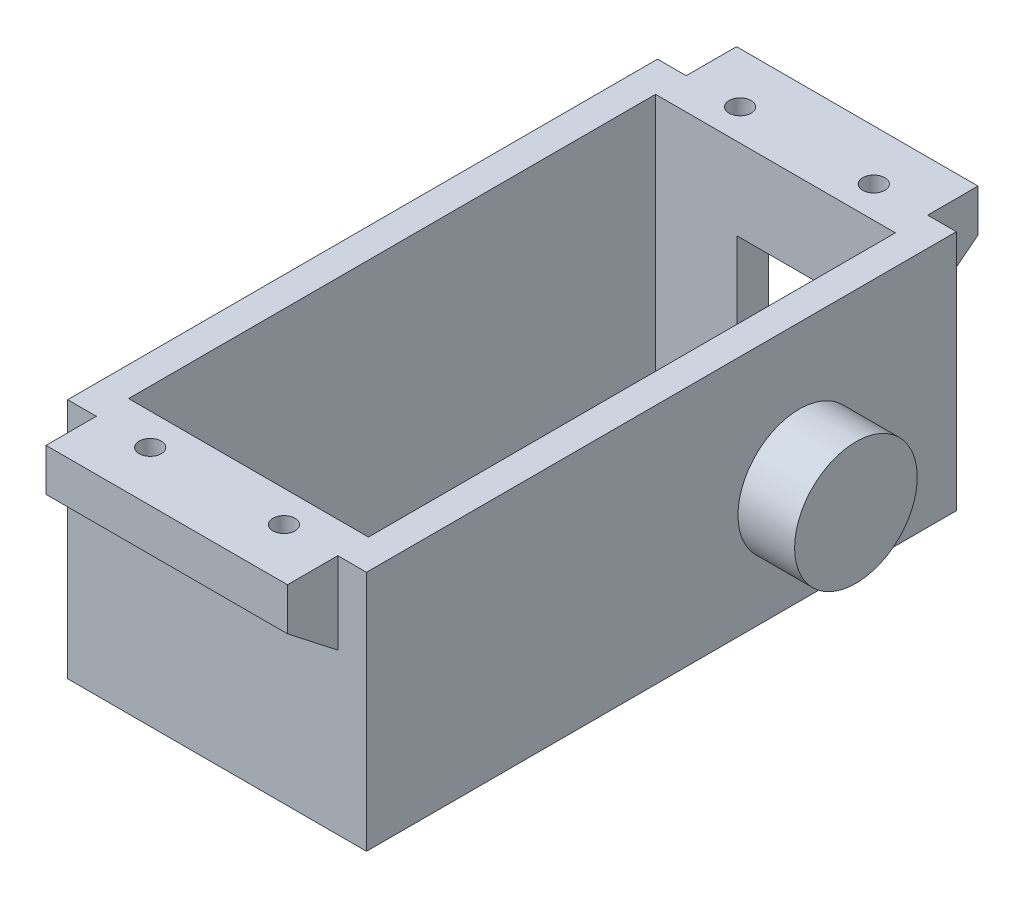
SolidWorks part; units mm, degrees
ref_plane "前视基准面" through (0, 0, 0) normal (0, 0, 1) x (1, 0, 0)
ref_plane "上视基准面" through (0, 0, 0) normal (0, 1, 0) x (1, 0, 0)
ref_plane "右视基准面" through (0, 0, 0) normal (1, 0, 0) x (0, 0, -1)
other "Configuration Table"
sketch "草图1" plane through (0, 0, 0) normal (0, 1, 0) x (1, 0, 0)
  line L1 (19, -37.5) -> (-19, -37.5)
  line L2 (19, -37.5) -> (19, 37.5)
  line L3 (19, 37.5) -> (-19, 37.5)
  line L4 (-19, -37.5) -> (-19, 37.5)
  line L5 (19, -37.5) -> (-19, 37.5) construction
  line L6 (19, 37.5) -> (-19, -37.5) construction
  point P0 (0, 0)
  dimension "D1" = 75
  dimension "D2" = 38
extrude "凸台-拉伸1" add sketch "草图1" along normal blind 30.73
sketch "草图2" plane through (-19, 0, 0) normal (-1, 0, 0) x (0, 0, 1)
  line L1 (-37.5, 30.73) -> (-37.5, 0) construction
  line L3 (-37.5, 0) -> (37.5, 0) construction
  circle A0 centre (-17.53, 13.39) radius 7.8
  point P2 (-17.53, 21.19)
  point P3 (-17.53, 5.59)
  point P4 (-25.33, 13.39)
  point P5 (-9.73, 13.39)
  point P10 (0, 0)
  dimension "D2" = 15.6
  dimension "D1" = 12.17
  dimension "D3" = 5.59
extrude "凸台-拉伸2" add sketch "草图2" along normal blind 7.2
sketch "草图3" plane through (0, 0, -37.5) normal (0, 0, -1) x (-1, 0, 0)
  line L0 (-19, 30.73) -> (19, 30.73) construction
  line L1 (15.35, 20.33) -> (-15.35, 20.33)
  line L2 (15.35, 20.33) -> (15.35, 30.73)
  line L3 (15.35, 30.73) -> (-15.35, 30.73)
  line L4 (-15.35, 20.33) -> (-15.35, 30.73)
  line L5 (15.35, 20.33) -> (-15.35, 30.73) construction
  line L6 (15.35, 30.73) -> (-15.35, 20.33) construction
  point P0 (0, 25.53)
  point P7 (0, 0)
  dimension "D1" = 30.7
  dimension "D2" = 10.4
extrude "凸台-拉伸3" add sketch "草图3" along normal blind 6.4
sketch "草图5" plane through (0, 30.73, 0) normal (0, 1, 0) x (1, 0, 0)
  line L1 (15.25, -33.5) -> (-15.25, -33.5)
  line L2 (15.25, -33.5) -> (15.25, 33.5)
  line L3 (15.25, 33.5) -> (-15.25, 33.5)
  line L4 (-15.25, -33.5) -> (-15.25, 33.5)
  line L5 (15.25, -33.5) -> (-15.25, 33.5) construction
  line L6 (15.25, 33.5) -> (-15.25, -33.5) construction
  point P0 (0, 0)
  dimension "D1" = 67
  dimension "D2" = 30.5
extrude "切除-拉伸1" cut sketch "草图5" against normal through all
mirror "镜向2" about plane through (0, 0, 0) normal (1, 0, 0) of "凸台-拉伸2"
sketch "草图6" plane through (0, 0, -37.5) normal (0, 0, -1) x (-1, 0, 0)
  line L0 (-19, 0) -> (19, 0) construction
  line L1 (4.9, 0) -> (-4.9, 0)
  line L2 (4.9, 0) -> (4.9, 20.33)
  line L3 (4.9, 20.33) -> (-4.9, 20.33)
  line L4 (-4.9, 0) -> (-4.9, 20.33)
  line L5 (4.9, 0) -> (-4.9, 20.33) construction
  line L6 (4.9, 20.33) -> (-4.9, 0) construction
  line L7 (-15.35, 20.33) -> (15.35, 20.33) construction
  point P0 (0, 10.165)
  point P7 (0, 0)
  dimension "D1" = 9.8
extrude "切除-拉伸2" cut sketch "草图6" against normal up to next
sketch "草图7" plane through (15.35, 0, 0) normal (1, 0, 0) x (0, 0, -1)
  line L0 (37.5, 20.33) -> (43.9, 25.3302)
  line L1 (43.9, 30.73) -> (43.9, 20.33) construction
  line L2 (43.9, 25.3302) -> (43.9, 20.33)
  line L3 (43.9, 20.33) -> (37.5, 20.33) construction
  line L4 (43.9, 20.33) -> (37.5, 20.33)
  line L5 (37.5, 30.73) -> (37.5, 0) construction
  dimension "D1" = 128
extrude "切除-拉伸3" cut sketch "草图7" against normal up to next
mirror "镜向4" about plane through (0, 0, 0) normal (0, 0, 1) of "切除-拉伸3", "凸台-拉伸3"
sketch "草图8" plane through (0, 30.73, 0) normal (0, 1, 0) x (1, 0, 0)
  line L0 (-15.35, 37.5) -> (15.35, 37.5) construction
  line L1 (19, 37.5) -> (15.35, 37.5) construction
  line L2 (0, 37.5) -> (0, 43.9) construction
  line L3 (-15.35, 43.9) -> (15.35, 43.9) construction
  line L4 (-19, 0) -> (19, 0) construction
  line L5 (-19, 37.5) -> (-19, -37.5) construction
  line L6 (19, -37.5) -> (19, 37.5) construction
  circle A0 centre (-8.5, 37.5) radius 1.4
  circle A1 centre (8.5, 37.5) radius 1.4
  circle A2 centre (8.5, -37.5) radius 1.4
  circle A3 centre (-8.5, -37.5) radius 1.4
  dimension "D3" = 2.8
  dimension "D1" = 17
  dimension "D2" = 75
extrude "切除-拉伸4" cut sketch "草图8" against normal blind 7.4
